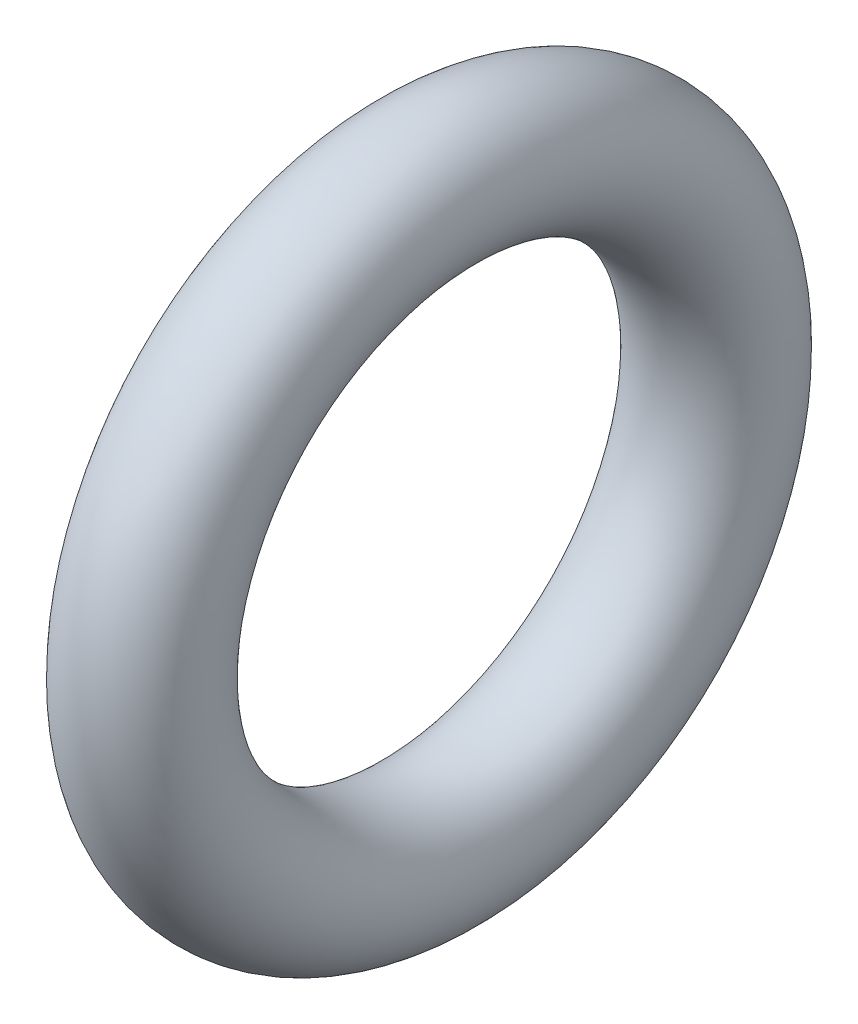
SolidWorks part; units mm, degrees
ref_plane "Front Plane" through (0, 0, 0) normal (0, 0, 1) x (1, 0, 0)
ref_plane "Top Plane" through (0, 0, 0) normal (0, 1, 0) x (1, 0, 0)
ref_plane "Right Plane" through (0, 0, 0) normal (1, 0, 0) x (0, 0, -1)
sketch "Sketch1" plane through (0, 0, 0) normal (0, 1, 0) x (1, 0, 0)
  line L0 (-95.4448, -0.3095) -> (-84.6535, -0.3095) construction
  circle A0 centre (-91.0923, -3.447) radius 0.7375
  point P2 (-91.0923, -2.7095)
  point P5 (-91.0923, -4.1845)
  dimension "D1" = 2.4
  dimension "D2" = 3.875
revolve "Revolve1" add sketch "Sketch1" angle 360 about L0
